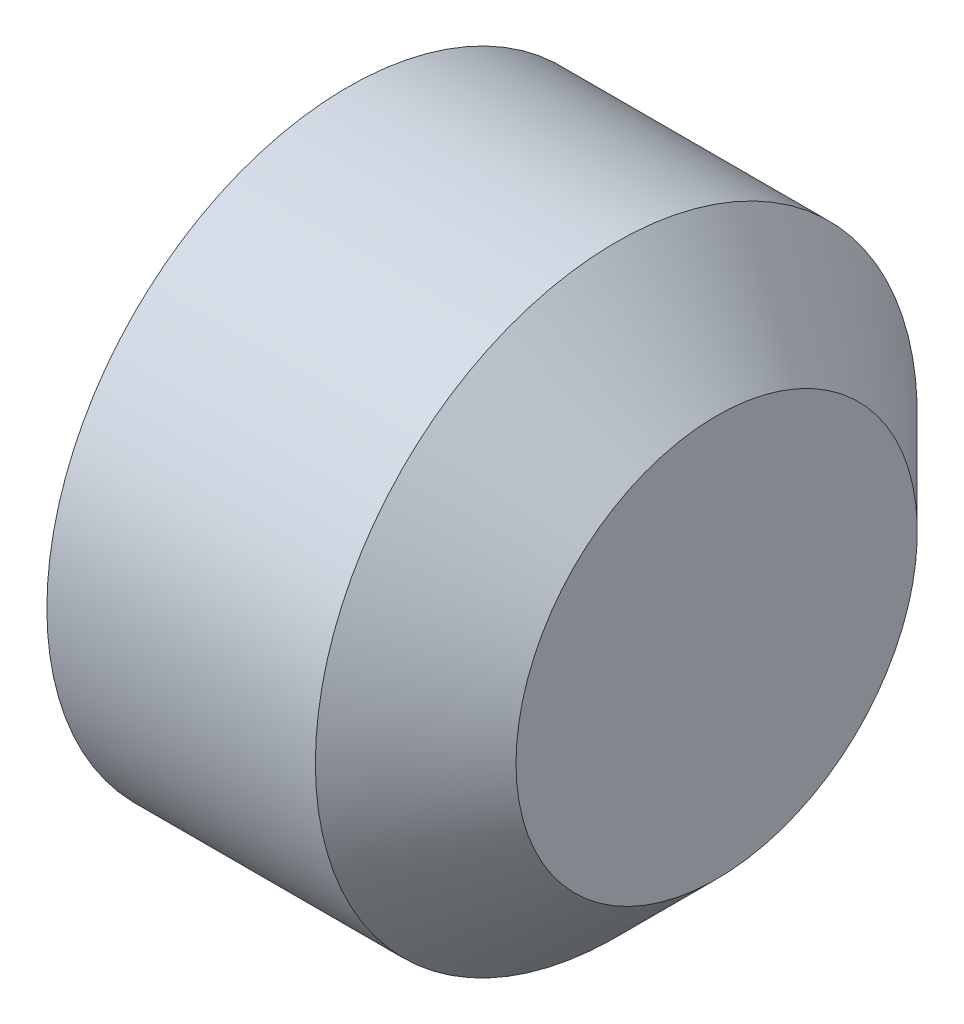
SolidWorks part; units mm, degrees
revolve "BaseBody" add sketch "BodySke" angle 360 about L5
sketch "BodySke" plane through (0, 0, 0) normal (0, 0, 1) x (1, 0, 0)
  line L0 (0, 0) -> (0, 1.2195)
  line L1 (0, 1.2195) -> (0.1619, 1.5)
  line L2 (0.1619, 1.5) -> (1.5, 1.5)
  line L3 (1.5, 1.5) -> (2, 1)
  line L4 (2, 0) -> (0, 0)
  line L5 (-12.7, 0) -> (88.9, 0) construction
  line L6 (2, 1) -> (2, 0)
  line L7 (2, 1) -> (2, 10.525) construction
  line L8 (0, -1.2195) -> (0.1619, -1.5) construction
  line L9 (0.5, 15.875) -> (0.5, -3.175) construction
  line L10 (1.5, -1.5) -> (2, -1) construction
  dimension "Diameter" = 3
  dimension "Drive_ch_ang" = 60
  dimension "Minor_dia" = 2.439
  dimension "Cup_nose_ang" = 45
  dimension "Cup_dia" = 2
  dimension "Length" = 2
  dimension "Advance" = 0.5
cosmetic thread "ThreadCosmetic" [suppressed] parameters "Thread_minor"=2.439
ref_plane "Plane1" through (0, 0, 0) normal (0, 0, 1) x (1, 0, 0)
ref_plane "Plane2" through (0, 0, 0) normal (0, 1, 0) x (1, 0, 0)
ref_plane "Plane3" through (0, 0, 0) normal (1, 0, 0) x (0, 0, -1)
sketch "Sketch2" plane through (0, 0, 0) normal (-1, 0, 0) x (0, 0, 1)
  line L0 (0.433, 0.75) -> (-0.433, 0.75)
  line L1 (-0.433, 0.75) -> (-0.866, 0)
  line L2 (0.433, 0.75) -> (0.866, 0)
  line L3 (0.433, -0.75) -> (0.866, 0)
  line L4 (0.433, -0.75) -> (-0.433, -0.75)
  line L5 (-0.433, -0.75) -> (-0.866, 0)
  dimension "Hex_size" = 1.5
  dimension "D2" = 0.75
  dimension "D3" = 0.75
extrude "Hex" cut sketch "Sketch2" against normal blind 1.2
sketch "ThdSchSke" plane through (0, 0, 0) normal (0, 0, 1) x (1, 0, 0)
  line L0 (0.1619, -1.2195) -> (-0.0345, -1.5)
  line L1 (0.1619, -1.2195) -> (0.3584, -1.5)
  line L2 (0.3584, -1.5) -> (0.3584, -1.875)
  line L3 (-3.175, 0) -> (5.1513, 0) construction
  line L5 (0.3584, -1.875) -> (-0.0345, -1.875)
  line L6 (-0.0345, -1.875) -> (-0.0345, -1.5)
  line L8 (0.1619, 1.5) -> (0.1619, -1.5) construction
  dimension "Thread_minor" = 2.439
  dimension "Diameter" = 3
revolve "ThreadSchematic" [suppressed] cut sketch "ThdSchSke" angle 360 about L3
pattern_linear "ThdSchPat" [suppressed]
equation "\"D2@Sketch2\" = \"Hex_size@Sketch2\" / 2"
equation "\"D3@Sketch2\" = \"Hex_size@Sketch2\" / 2"
equation "\"Thread_minor@ThreadCosmetic\" = \"Minor_dia@BodySke\""
equation "\"Thread_minor@ThdSchSke\" = \"Thread_minor@ThreadCosmetic\""
equation "\"Diameter@ThdSchSke\" = \"Diameter@BodySke\""
equation "\"Overcut@ThdSchSke\" = \"Diameter@BodySke\" * 1.25"
equation "\"Num_threads@ThdSchPat\" = int( (\"Length@BodySke\" - ( ( ( \"Diameter@BodySke\" - \"Minor_dia@BodySke\" ) * 0.5 ) / tan( \"Drive_ch_ang@BodySke\" * 0.017453292 ) ) - ( ( ( \"Diameter@BodySke\" - \"Cup_dia@BodySke\" ) * 0.5 ) * tan( \"Cup_nose_ang@BodySke\" * 0.017453292 ) ) ) / \"Advance@BodySke\" + 0.999 )  + 1"
equation "\"Advance@ThdSchPat\" = (\"Length@BodySke\" - ( ( ( \"Diameter@BodySke\" - \"Minor_dia@BodySke\" ) * 0.5 ) / tan( \"Drive_ch_ang@BodySke\" * 0.017453292 ) ) - ( ( ( \"Diameter@BodySke\" - \"Cup_dia@BodySke\" ) * 0.5 ) * tan( \"Cup_nose_ang@BodySke\" * 0.017453292 ) ) ) /  (\"Num_threads@ThdSchPat\" - 1) 'relax it"
equation "' \"Num_threads@ThdSchPat\" = \"Num_threads@ThdSchPat\" - sgn( \"Num_threads@ThdSchPat\" - 1) '---chamfered tips only---"
